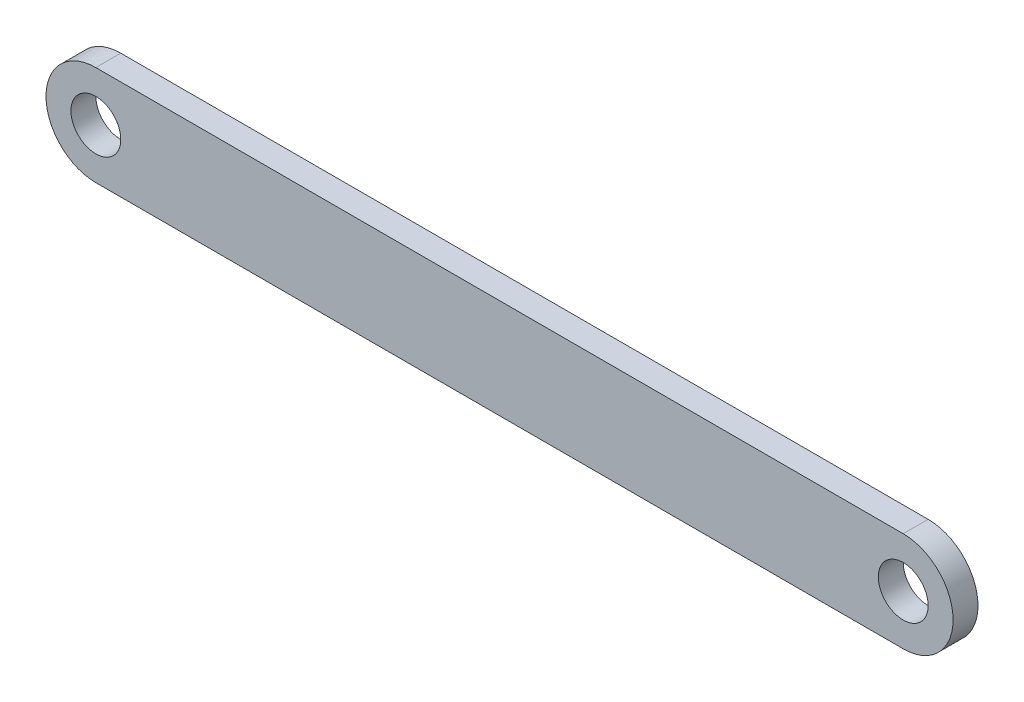
SolidWorks part; units mm, degrees
ref_plane "Спереди" through (0, 0, 0) normal (0, 0, 1) x (1, 0, 0)
ref_plane "Сверху" through (0, 0, 0) normal (0, 1, 0) x (1, 0, 0)
ref_plane "Справа" through (0, 0, 0) normal (1, 0, 0) x (0, 0, -1)
sketch "Эскиз1" plane through (0, 0, 0) normal (0, 0, 1) x (1, 0, 0)
  line L0 (0, 0) -> (-32.398, 0)
  line L1 (-32.398, -2) -> (0, -2)
  line L2 (-32.398, 2) -> (0, 2)
  circle A0 centre (-32.398, 0) radius 1
  circle A1 centre (0, 0) radius 1
  circle A2 centre (-32.398, 0) radius 2
  circle A3 centre (0, 0) radius 2
  dimension "D1" = 32.398
extrude "Бобышка-Вытянуть1" add sketch "Эскиз1" along normal mid plane 1
sketch "Sketch1" plane through (0, 0, 0) normal (0, 0, 1) x (1, 0, 0)
  line L0 (0, 0) -> (-14, 0)
  line L1 (-14, 0) -> (-14, 1.5)
  line L2 (-25.5979, -2) -> (-2.0642, -2)
  line L3 (-14, 0) -> (-32.398, 0)
  line L7 (-14, 1.5) -> (-20.4712, -4.9712)
  line L11 (0, 2) -> (-30.8022, 2)
  line L12 (-14, 1.5) -> (-7.5288, -4.9712)
  line L13 (-20.4712, -4.9712) -> (-7.5288, -4.9712)
  line L14 (-15.6569, 5.5) -> (-30.1281, -8.9712)
  line L15 (-30.1281, -8.9712) -> (2.1281, -8.9712)
  line L16 (-12.3431, 5.5) -> (2.1281, -8.9712)
  line L17 (-14, 1.5) -> (-14, 5.5)
  line L18 (-14, 5.5) -> (-15.6569, 5.5)
  line L19 (-14, 5.5) -> (-12.3431, 5.5)
  line L21 (-14, 7.1569) -> (-30.1281, -8.9712) construction
  line L22 (-14, 7.1569) -> (2.1281, -8.9712) construction
  point P6 (-9.7278, -2.9956)
  point P9 (-14.7071, 0.7071)
  point P10 (-13.2929, 0.7071)
  point P11 (-21.4142, -2.5858)
  point P15 (-16, 0)
  point P22 (-10, 0)
  dimension "D1" = 4
  dimension "D4" = 14
  dimension "D2" = 1.5
